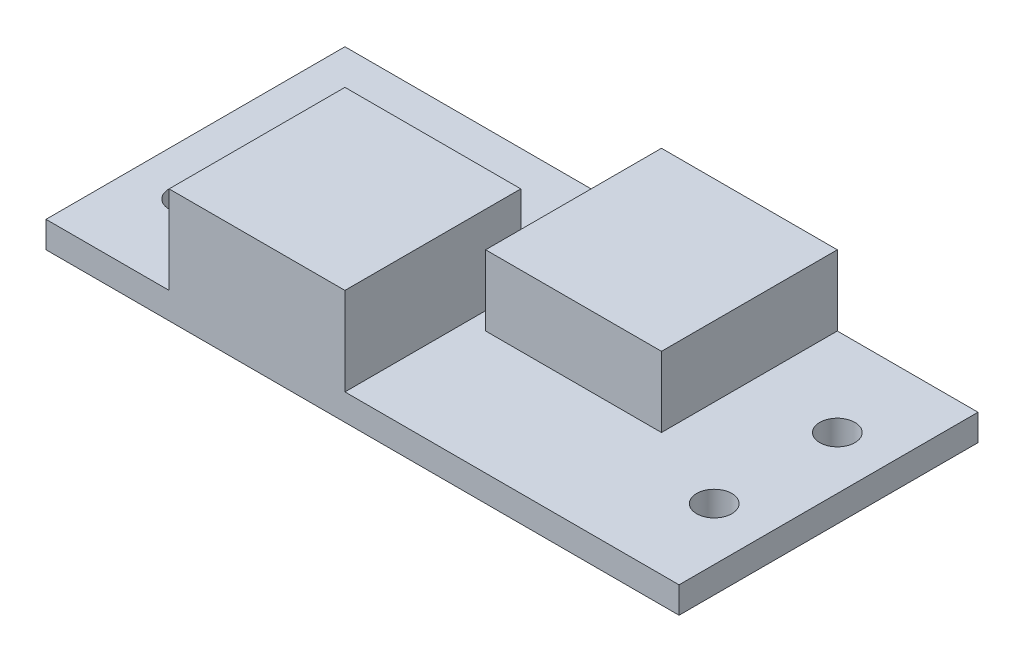
SolidWorks part; units mm, degrees
ref_plane "Front Plane" through (0, 0, 0) normal (0, 0, 1) x (1, 0, 0)
ref_plane "Top Plane" through (0, 0, 0) normal (0, 1, 0) x (1, 0, 0)
ref_plane "Right Plane" through (0, 0, 0) normal (1, 0, 0) x (0, 0, -1)
sketch "Sketch1" plane through (0, 0, 0) normal (0, 1, 0) x (1, 0, 0)
  line L1 (0, 0) -> (36, 0)
  line L2 (0, 0) -> (0, -17)
  line L3 (0, -17) -> (36, -17)
  line L4 (36, 0) -> (36, -17)
  dimension "D1" = 17
  dimension "D2" = 36
  dimension "D3" = 0
  dimension "D4" = 0
extrude "Boss-Extrude1" add sketch "Sketch1" along normal blind 1.5
sketch "Sketch2" plane through (0, 1.5, 0) normal (0, 1, 0) x (1, 0, 0)
  line L0 (36, 0) -> (0, 0) construction
  line L1 (28, 0) -> (18, 0)
  line L2 (28, 0) -> (28, -10)
  line L3 (28, -10) -> (18, -10)
  line L4 (18, 0) -> (18, -10)
  line L5 (36, -17) -> (36, 0) construction
  dimension "D1" = 10
  dimension "D2" = 10
  dimension "D3" = 8
extrude "Boss-Extrude2" add sketch "Sketch2" along normal blind 4
sketch "Sketch3" plane through (0, 1.5, 0) normal (0, 1, 0) x (1, 0, 0)
  line L0 (0, -17) -> (36, -17) construction
  line L1 (7, -17) -> (17, -17)
  line L2 (7, -17) -> (7, -7)
  line L3 (7, -7) -> (17, -7)
  line L4 (17, -17) -> (17, -7)
  line L5 (0, 0) -> (0, -17) construction
  dimension "D1" = 10
  dimension "D2" = 10
  dimension "D3" = 7
extrude "Boss-Extrude3" add sketch "Sketch3" along normal blind 5
sketch "Sketch4" plane through (0, 1.5, 0) normal (0, 1, 0) x (1, 0, 0)
  line L0 (18, 0) -> (0, 0) construction
  line L1 (0, 0) -> (0, -17) construction
  circle A0 centre (3, -5) radius 1
  point P2 (3.4142, -3.6665)
  dimension "D1" = 2
  dimension "D2" = 5
  dimension "D3" = 3
extrude "Cut-Extrude1" cut sketch "Sketch4" against normal blind 5
pattern_linear "LPattern1" count 2 spacing 7 along (0, 0, 1) of "Cut-Extrude1"
pattern_linear "LPattern2" count 2 spacing 30 along (1, 0, 0) of "LPattern1", "Cut-Extrude1"
